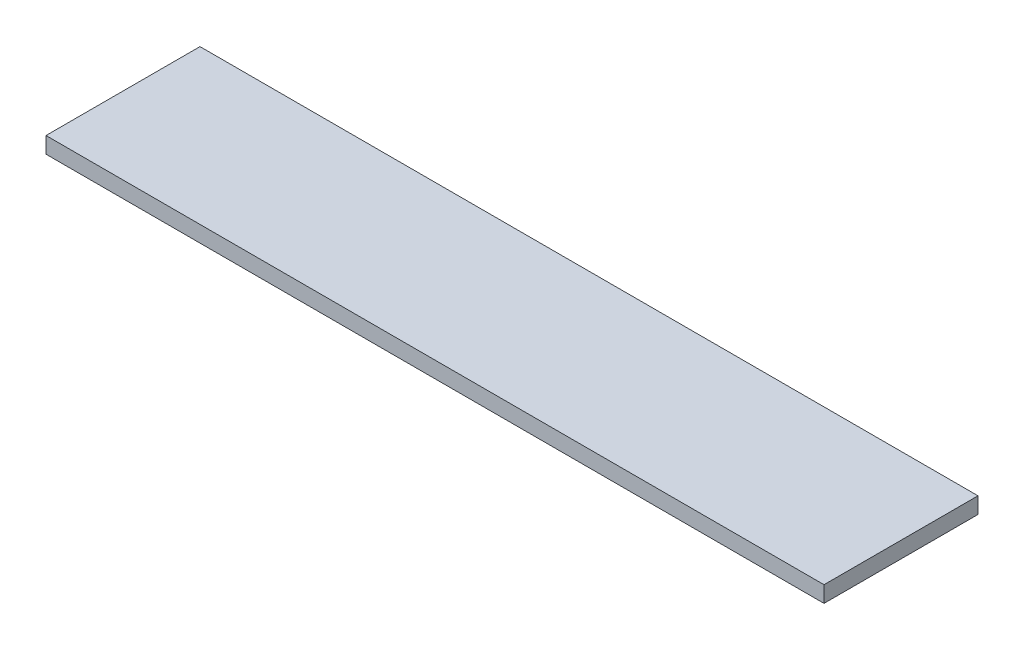
SolidWorks part; units mm, degrees
ref_plane "Front Plane" through (0, 0, 0) normal (0, 0, 1) x (1, 0, 0)
ref_plane "Top Plane" through (0, 0, 0) normal (0, 1, 0) x (1, 0, 0)
ref_plane "Right Plane" through (0, 0, 0) normal (1, 0, 0) x (0, 0, -1)
sketch "Sketch1" plane through (0, 0, 0) normal (0, 1, 0) x (1, 0, 0)
  line L0 (-304.8, -120.65) -> (-304.8, 0) construction
  line L1 (304.8, -120.65) -> (-304.8, -120.65)
  line L2 (304.8, -120.65) -> (304.8, 0)
  line L3 (304.8, 0) -> (-304.8, 0)
  line L4 (-304.8, -120.65) -> (-304.8, 0)
  line L5 (304.8, -120.65) -> (-304.8, 0) construction
  line L6 (304.8, 0) -> (-304.8, -120.65) construction
  line L7 (292.1, -120.65) -> (304.8, -120.65) construction
  point P0 (0, -60.325)
extrude "Boss-Extrude1" add sketch "Sketch1" along normal blind 12.7
